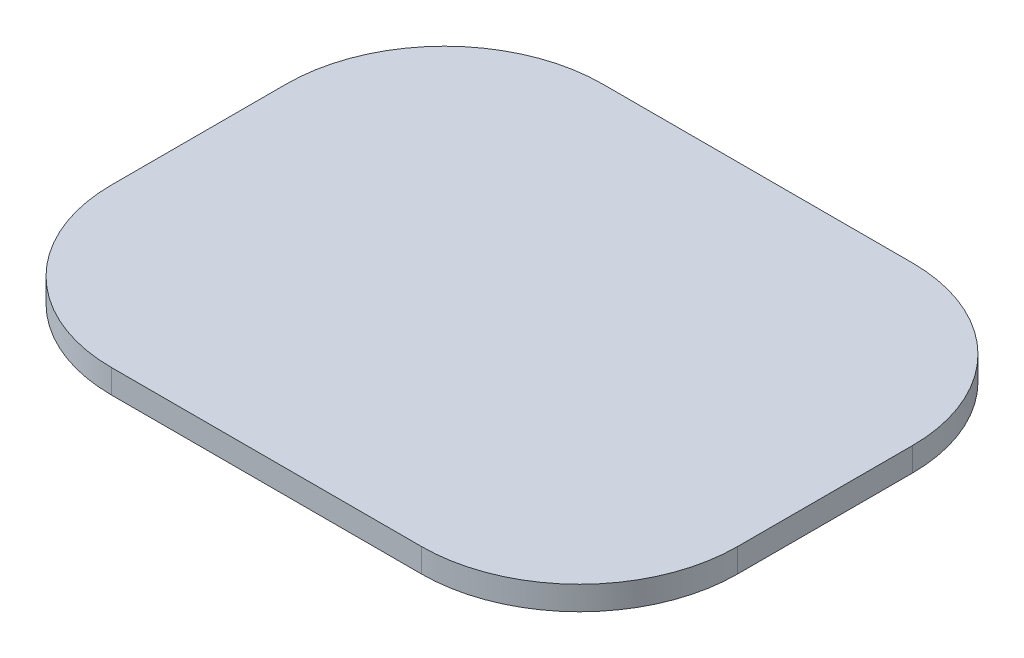
SolidWorks part; units mm, degrees
ref_plane "Front Plane" through (0, 0, 0) normal (0, 0, 1) x (1, 0, 0)
ref_plane "Top Plane" through (0, 0, 0) normal (0, 1, 0) x (1, 0, 0)
ref_plane "Right Plane" through (0, 0, 0) normal (1, 0, 0) x (0, 0, -1)
sketch "Sketch1" plane through (0, 0, 0) normal (0, 1, 0) x (1, 0, 0)
  line L0 (0, 31) -> (0, -31) construction
  line L1 (-19.5, 31) -> (19.5, 31) construction
  line L2 (-39.5, 11) -> (-39.5, -11) construction
  line L3 (-19.5, -31) -> (19.5, -31) construction
  line L4 (39.5, 11) -> (39.5, -11) construction
  line L5 (-19.5, 30.9) -> (19.5, 30.9)
  line L6 (39.4, 11) -> (39.4, -11)
  line L7 (-19.5, -30.9) -> (19.5, -30.9)
  line L8 (-39.4, 11) -> (-39.4, -11)
  arc A0 (19.5, 31) -> (39.5, 11) centre (19.5, 11) cw construction
  arc A1 (19.5, -31) -> (39.5, -11) centre (19.5, -11) ccw construction
  arc A2 (-39.5, -11) -> (-19.5, -31) centre (-19.5, -11) ccw construction
  arc A3 (-19.5, 31) -> (-39.5, 11) centre (-19.5, 11) ccw construction
  arc A4 (19.5, 30.9) -> (39.4, 11) centre (19.5, 11) cw
  arc A5 (19.5, -30.9) -> (39.4, -11) centre (19.5, -11) ccw
  arc A6 (-39.4, -11) -> (-19.5, -30.9) centre (-19.5, -11) ccw
  arc A7 (-19.5, 30.9) -> (-39.4, 11) centre (-19.5, 11) ccw
  point P6 (39.5, 31)
  point P9 (39.5, -31)
  point P14 (-39.5, 31)
  dimension "D3" = 20
  dimension "D1" = 79
  dimension "D2" = 62
  dimension "D4" = 0.1
extrude "Boss-Extrude1" add sketch "Sketch1" along normal mid plane 3
